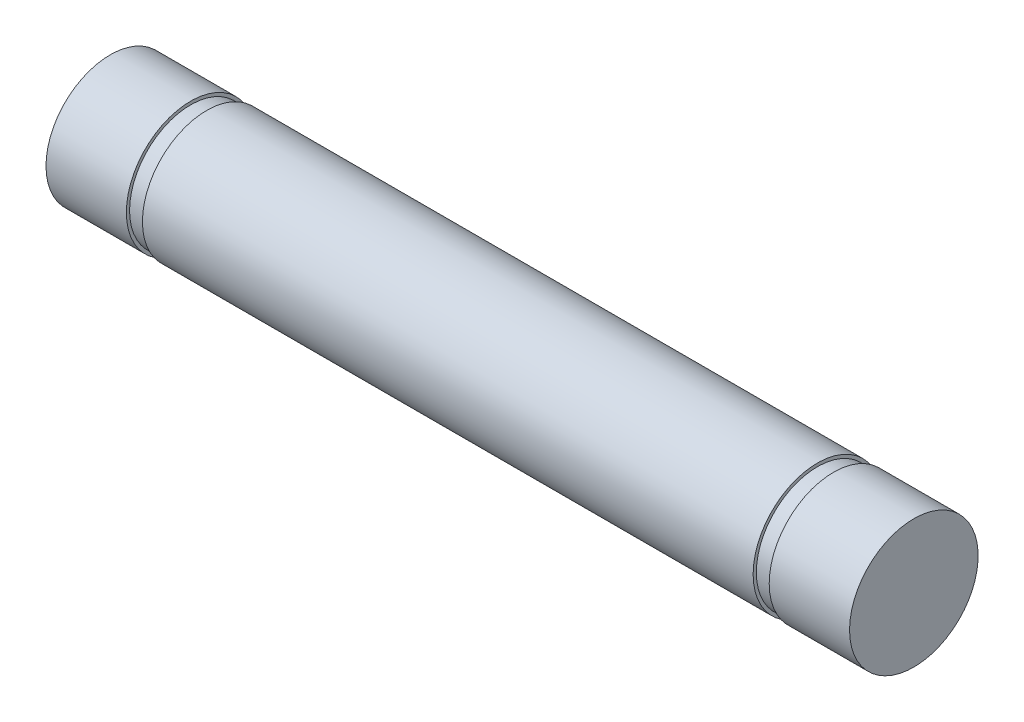
SolidWorks part; units mm, degrees
ref_plane "Ön Düzlem" through (0, 0, 0) normal (0, 0, 1) x (1, 0, 0)
ref_plane "Üst Düzlem" through (0, 0, 0) normal (0, 1, 0) x (1, 0, 0)
ref_plane "Sağ Düzlem" through (0, 0, 0) normal (1, 0, 0) x (0, 0, -1)
sketch "Çizim1" plane through (0, 0, 0) normal (0, 0, 1) x (1, 0, 0)
  line L0 (12.5, 0) -> (12.5, 2) construction
  line L1 (0, 0) -> (25, 0)
  line L2 (0, 0) -> (0, 2)
  line L3 (0, 2) -> (2.5, 2)
  line L4 (25, 0) -> (25, 2)
  line L5 (3, 1.9) -> (2.5, 1.9)
  line L6 (3, 1.9) -> (3, 2)
  line L7 (3, 2) -> (22, 2)
  line L8 (2.5, 1.9) -> (2.5, 2)
  line L9 (22, 1.9) -> (22.5, 1.9)
  line L10 (22.5, 1.9) -> (22.5, 2)
  line L11 (22.5, 2) -> (25, 2)
  line L12 (22, 1.9) -> (22, 2)
  dimension "D1" = 2
  dimension "D2" = 25
  dimension "D3" = 2.5
  dimension "D4" = 0.5
  dimension "D5" = 0.1
revolve "Döndür1" add sketch "Çizim1" angle 360 about L1
